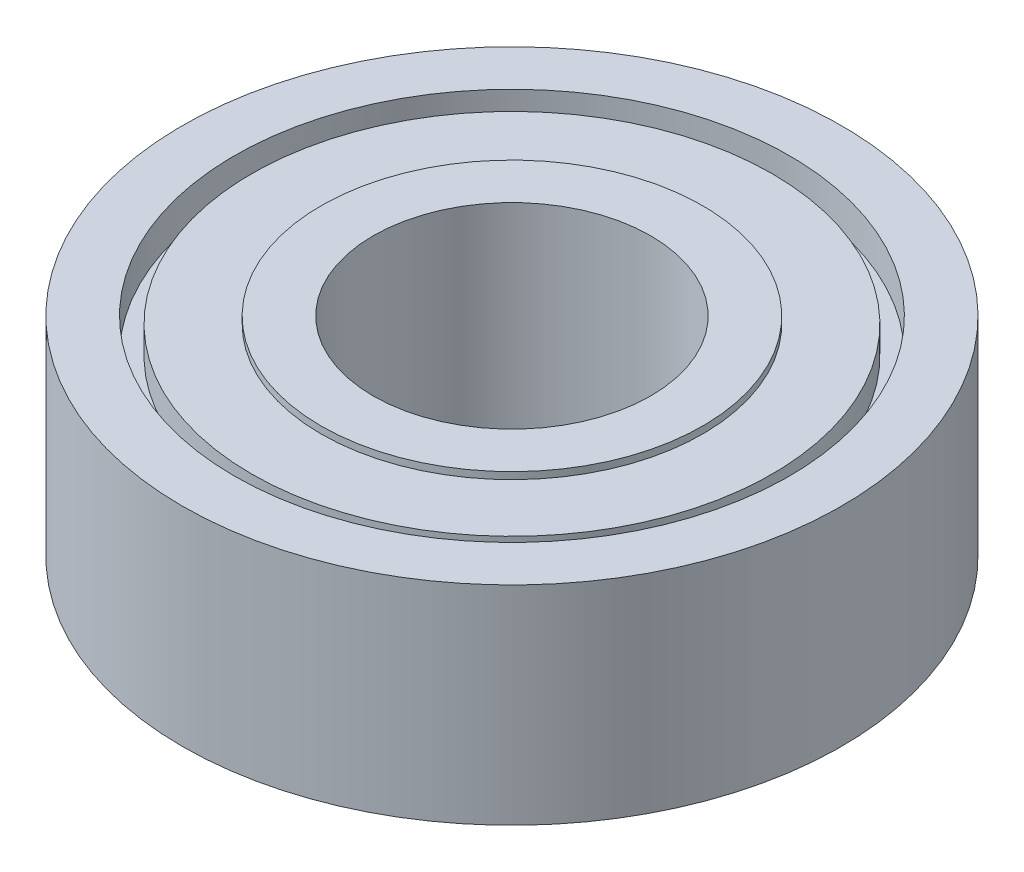
SolidWorks part; units mm, degrees
ref_plane "Front Plane" through (0, 0, 0) normal (0, 0, 1) x (1, 0, 0)
ref_plane "Top Plane" through (0, 0, 0) normal (0, 1, 0) x (1, 0, 0)
ref_plane "Right Plane" through (0, 0, 0) normal (1, 0, 0) x (0, 0, -1)
sketch "Sketch1" plane through (0, 0, 0) normal (0, 1, 0) x (1, 0, 0)
  circle A0 centre (0, 0) radius 4
  circle A1 centre (0, 0) radius 5.5
  dimension "D1" = 8
  dimension "D2" = 11
extrude "Boss-Extrude1" add sketch "Sketch1" along normal mid plane 6
sketch "Sketch3" plane through (0, 0, 0) normal (0, 1, 0) x (1, 0, 0)
  circle A0 centre (0, 0) radius 5.5
  circle A1 centre (0, 0) radius 7.5
  dimension "D1" = 15
  dimension "D2" = 11
extrude "Boss-Extrude2" add sketch "Sketch3" along normal mid plane 5.6
sketch "Sketch4" plane through (0, 0, 0) normal (0, 1, 0) x (1, 0, 0)
  circle A0 centre (0, 0) radius 7.5
  circle A1 centre (0, 0) radius 1
  circle A2 centre (0, 0) radius 8
  dimension "D1" = 15
  dimension "D2" = 16
extrude "Boss-Extrude3" add sketch "Sketch4" along normal mid plane 4 contours A2 A0
sketch "Sketch5" plane through (0, 0, 0) normal (0, 1, 0) x (1, 0, 0)
  circle A0 centre (0, 0) radius 8
  circle A1 centre (0, 0) radius 9.5
  dimension "D1" = 16
  dimension "D2" = 19
extrude "Boss-Extrude4" add sketch "Sketch5" along normal mid plane 6
